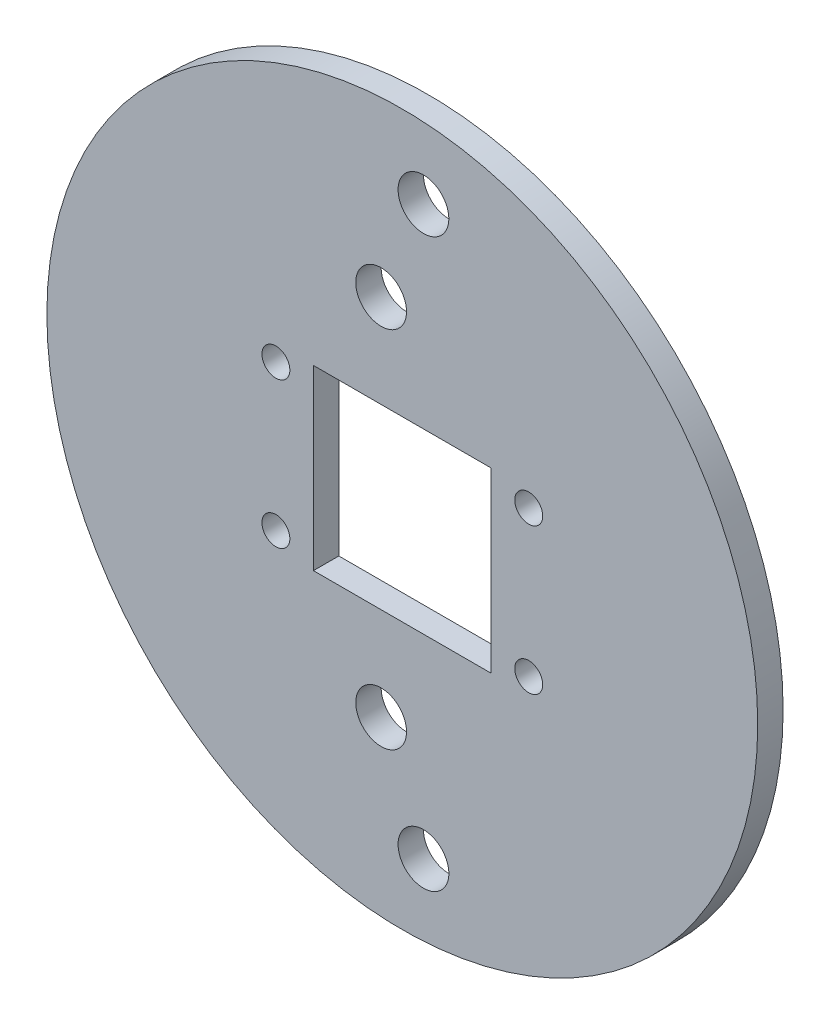
SolidWorks part; units mm, degrees
ref_plane "前视基准面" through (0, 0, 0) normal (0, 0, 1) x (1, 0, 0)
ref_plane "上视基准面" through (0, 0, 0) normal (0, 1, 0) x (1, 0, 0)
ref_plane "右视基准面" through (0, 0, 0) normal (1, 0, 0) x (0, 0, -1)
other "Configuration Table"
sketch "草图1" plane through (0, 0, 0) normal (0, 0, 1) x (1, 0, 0)
  line L0 (0, 10.5) -> (0, 25.6787) construction
  line L1 (-10.5, 10.5) -> (10.5, 10.5)
  line L2 (-10.5, 10.5) -> (-10.5, -10.5)
  line L3 (-10.5, -10.5) -> (10.5, -10.5)
  line L4 (10.5, 10.5) -> (10.5, -10.5)
  line L5 (-10.5, 10.5) -> (10.5, -10.5) construction
  line L6 (-10.5, -10.5) -> (10.5, 10.5) construction
  line L7 (0, 0) -> (14.9389, 0) construction
  circle A0 centre (0, 0) radius 42
  circle A1 centre (0, 0) radius 17.25 construction
  circle A3 centre (14.9389, 8.625) radius 1.65
  circle A4 centre (14.9389, -8.625) radius 1.65
  circle A6 centre (-14.9389, -8.625) radius 1.65
  circle A7 centre (-14.9389, 8.625) radius 1.65
  circle A9 centre (2.5, 33.5) radius 3
  circle A10 centre (-2.5, 21.5) radius 3
  circle A11 centre (-2.5, -21.5) radius 3
  circle A12 centre (2.5, -33.5) radius 3
  point P18 (0, 0)
  point P24 (14.9389, 0)
  dimension "D1" = 84
  dimension "D2" = 34.5
  dimension "D3" = 11
  dimension "D7" = 12
  dimension "D4" = 6
  dimension "D8" = 6
  dimension "D5" = 21
  dimension "D6" = 21
  dimension "D9" = 5
  dimension "D10" = 2.5
extrude "凸台-拉伸1" add sketch "草图1" along normal blind 3
